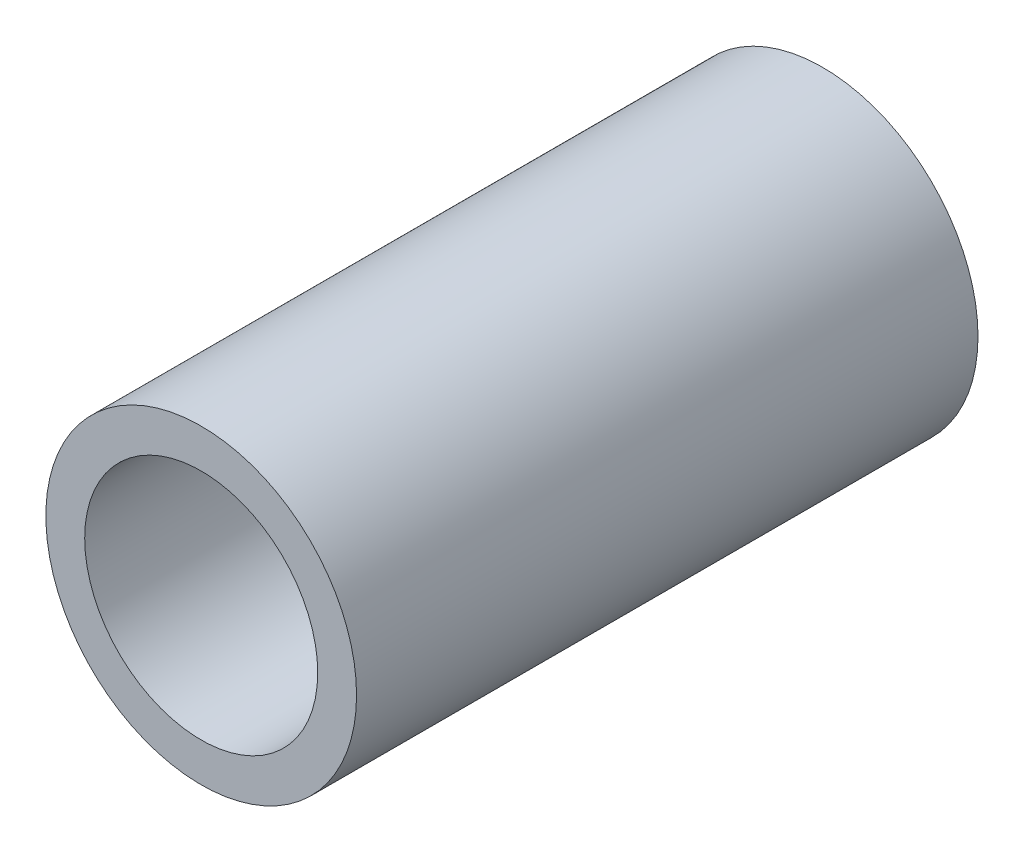
SolidWorks part; units mm, degrees
material "Tin Bearing Bronze"
ref_plane "Front Plane" through (0, 0, 0) normal (0, 0, 1) x (1, 0, 0)
ref_plane "Top Plane" through (0, 0, 0) normal (0, 1, 0) x (1, 0, 0)
ref_plane "Right Plane" through (0, 0, 0) normal (1, 0, 0) x (0, 0, -1)
sketch "Sketch1" plane through (0, 0, 0) normal (0, 0, 1) x (1, 0, 0)
  circle A0 centre (0, 0) radius 4.7625
  circle A1 centre (0, 0) radius 6.35
  dimension "D1" = 9.525
  dimension "D2" = 12.7
extrude "Boss-Extrude1" add sketch "Sketch1" along normal blind 25.4
